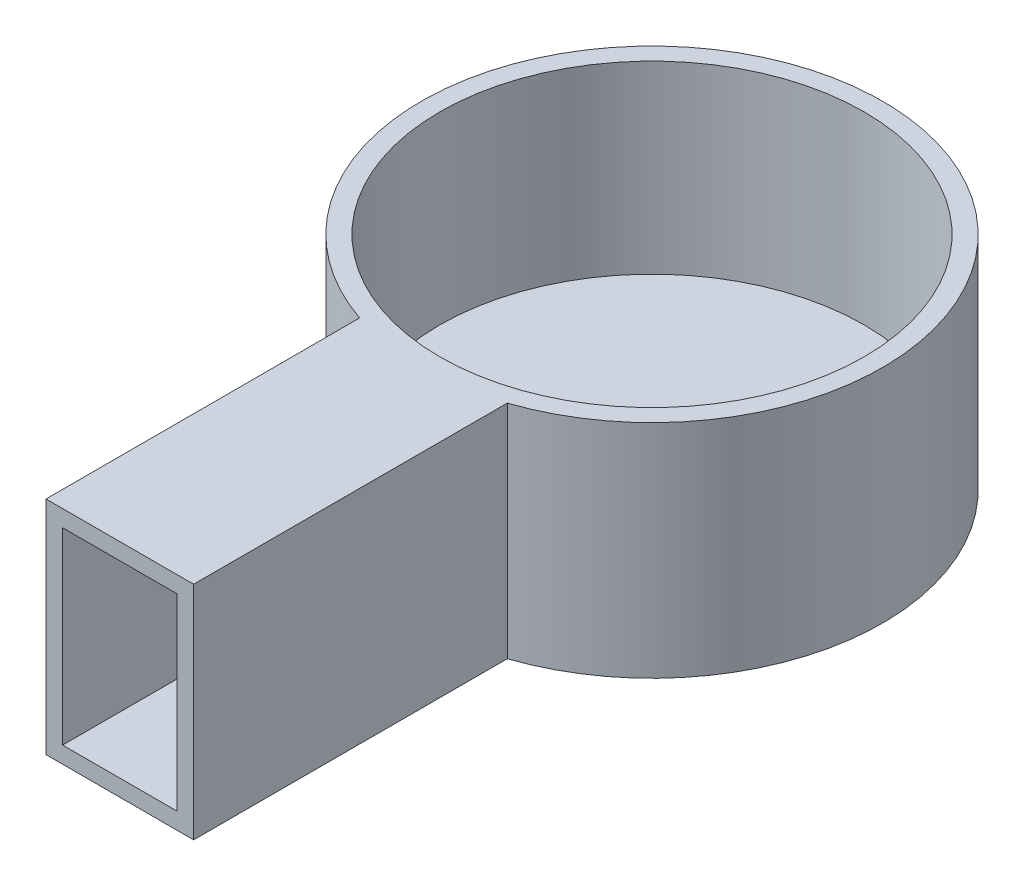
SolidWorks part; units mm, degrees
ref_plane "Plano frontal" through (0, 0, 0) normal (0, 0, 1) x (1, 0, 0)
ref_plane "Plano superior" through (0, 0, 0) normal (0, 1, 0) x (1, 0, 0)
ref_plane "Plano direito" through (0, 0, 0) normal (1, 0, 0) x (0, 0, -1)
sketch "Esboço2" plane through (0, 0, 0) normal (0, 0, 1) x (1, 0, 0)
  line L1 (4, -6) -> (-4, -6)
  line L2 (4, -6) -> (4, 6)
  line L3 (4, 6) -> (-4, 6)
  line L4 (-4, -6) -> (-4, 6)
  line L5 (4, -6) -> (-4, 6) construction
  line L6 (4, 6) -> (-4, -6) construction
  point P0 (0, 0)
  dimension "D1" = 8
  dimension "D2" = 12
extrude "Ressalto-extrusão1" add sketch "Esboço2" along normal blind 17
sketch "Esboço3" plane through (0, 0, 17) normal (0, 0, 1) x (1, 0, 0)
  line L1 (3.1, -5.1) -> (-3.1, -5.1)
  line L2 (3.1, -5.1) -> (3.1, 5.1)
  line L3 (3.1, 5.1) -> (-3.1, 5.1)
  line L4 (-3.1, -5.1) -> (-3.1, 5.1)
  line L5 (3.1, -5.1) -> (-3.1, 5.1) construction
  line L6 (3.1, 5.1) -> (-3.1, -5.1) construction
  point P0 (0, 0)
  dimension "D1" = 6.2
  dimension "D2" = 10.2
extrude "Corte-extrusão1" cut sketch "Esboço3" against normal blind 15
sketch "Esboço4" plane through (0, 6, 0) normal (0, 1, 0) x (1, 0, 0)
  line L0 (4, -17) -> (4, 0) construction
  circle A0 centre (0, 11.8427) radius 12.5
  dimension "D1" = 25
  dimension "D2" = 4
extrude "Ressalto-extrusão2" add sketch "Esboço4" against normal blind 12
sketch "Esboço5" plane through (0, 6, 0) normal (0, 1, 0) x (1, 0, 0)
  circle A0 centre (0, 11.8427) radius 11.5
  arc A1 (4, 0) -> (-4, 0) centre (0, 11.8427) ccw construction
  dimension "D1" = 23
  dimension "D2" = 0
extrude "Corte-extrusão2" cut sketch "Esboço5" against normal blind 10
